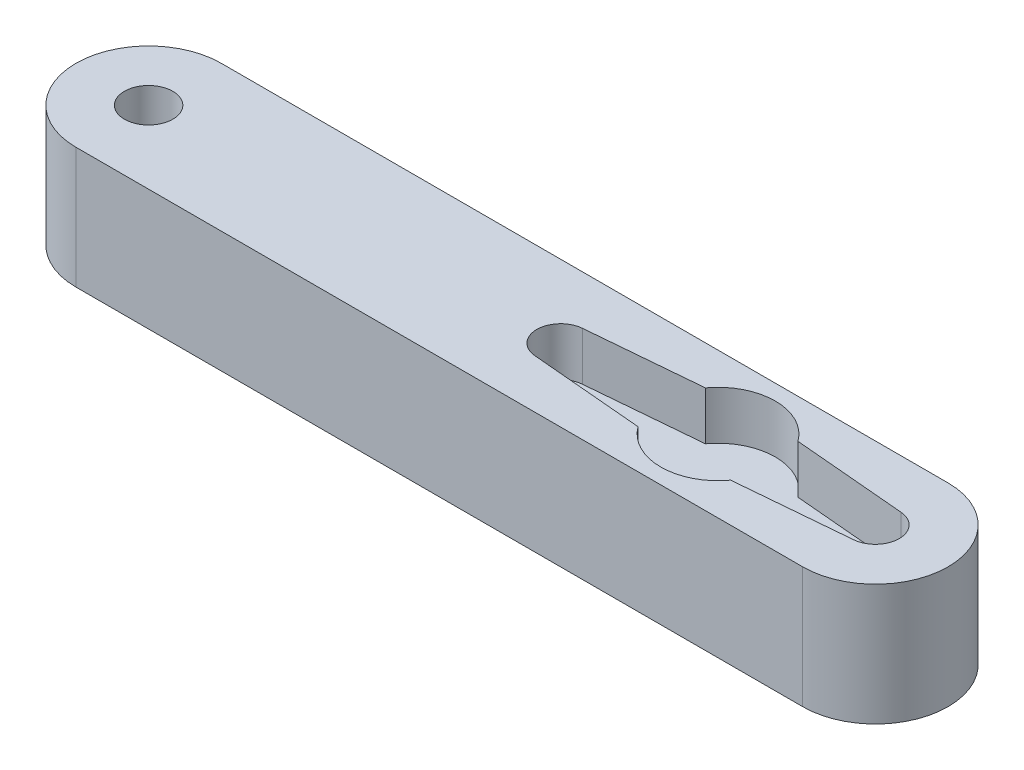
SolidWorks part; units mm, degrees
ref_plane "Front Plane" through (0, 0, 0) normal (0, 0, 1) x (1, 0, 0)
ref_plane "Top Plane" through (0, 0, 0) normal (0, 1, 0) x (1, 0, 0)
ref_plane "Right Plane" through (0, 0, 0) normal (1, 0, 0) x (0, 0, -1)
sketch "Sketch3" plane through (0, 0, 0) normal (0, 1, 0) x (1, 0, 0)
  line L0 (-31.75, 0) -> (44.45, 0) construction
  line L1 (-6.985, 0) -> (6.985, 0) construction
  line L2 (-31.75, 7.62) -> (44.45, 7.62)
  line L3 (-31.75, -7.62) -> (44.45, -7.62)
  arc A0 (-31.75, 7.62) -> (-31.75, -7.62) centre (-31.75, 0) ccw
  arc A1 (44.45, -7.62) -> (44.45, 7.62) centre (44.45, 0) ccw
  point P5 (6.35, 0)
  dimension "D2" = 7.62
  dimension "D1" = 76.2
  dimension "D3" = 31.75
extrude "Boss-Extrude1" add sketch "Sketch3" along normal blind 12.7
sketch "Sketch4" plane through (0, 12.7, 0) normal (0, 1, 0) x (1, 0, 0)
  circle A0 centre (-31.75, 0) radius 2.54
  dimension "D1" = 5.08
extrude "Cut-Extrude3" cut sketch "Sketch4" against normal through all
sketch "Sketch9" plane through (0, 12.7, 0) normal (0, 1, 0) x (-1, 0, 0)
  line L0 (-44.45, 0) -> (-11.45, 0) construction
  line L1 (-11.2321, -2.4905) -> (-23.0972, -3.5286)
  line L6 (-11.2321, 2.4905) -> (-23.0972, 3.5286)
  line L9 (-27.95, 6) -> (-27.95, -6) construction
  line L12 (-44.6679, 2.4905) -> (-32.8028, 3.5286)
  line L13 (-44.6679, -2.4905) -> (-32.8028, -3.5286)
  circle A2 centre (-27.95, 0) radius 2.54 construction
  arc A9 (-23.0972, 3.5286) -> (-32.8028, 3.5286) centre (-27.95, 0) ccw
  arc A10 (-11.2321, -2.4905) -> (-11.2321, 2.4905) centre (-11.45, 0) ccw
  arc A16 (-32.8028, -3.5286) -> (-23.0972, -3.5286) centre (-27.95, 0) ccw
  arc A22 (-44.6679, -2.4905) -> (-44.6679, 2.4905) centre (-44.45, 0) cw
  point P9 (-27.95, 0)
  dimension "D2" = 33
  dimension "D12" = 12
  dimension "D13" = 2.5
  dimension "D3" = 5.08
  dimension "D14" = 5
  dimension "D15" = 5
extrude "Cut-Extrude6" cut sketch "Sketch9" against normal blind 5.08 contours L12 A9 L6 A10 L1 A16 L13 A22
equation "\"TibiaLength\"= 5in"
equation "\"TibiaRadius\"= 0.3in"
equation "\"TibiaDistFromCentre\"= \"TibiaLength\" / 2"
equation "\"TibiaThickness\"= 0.5in"
equation "\"HoleRadius\"= 0.2in"
equation "\"D1@Sketch3\"= \"TibiaLength\" * 0.6"
equation "\"D2@Sketch3\"= \"TibiaRadius\""
equation "\"D3@Sketch3\"=\"TibiaDistFromCentre\"/2"
equation "\"D1@Boss-Extrude1\"= \"TibiaThickness\""
equation "\"D1@Sketch4\"= \"HoleRadius\""
